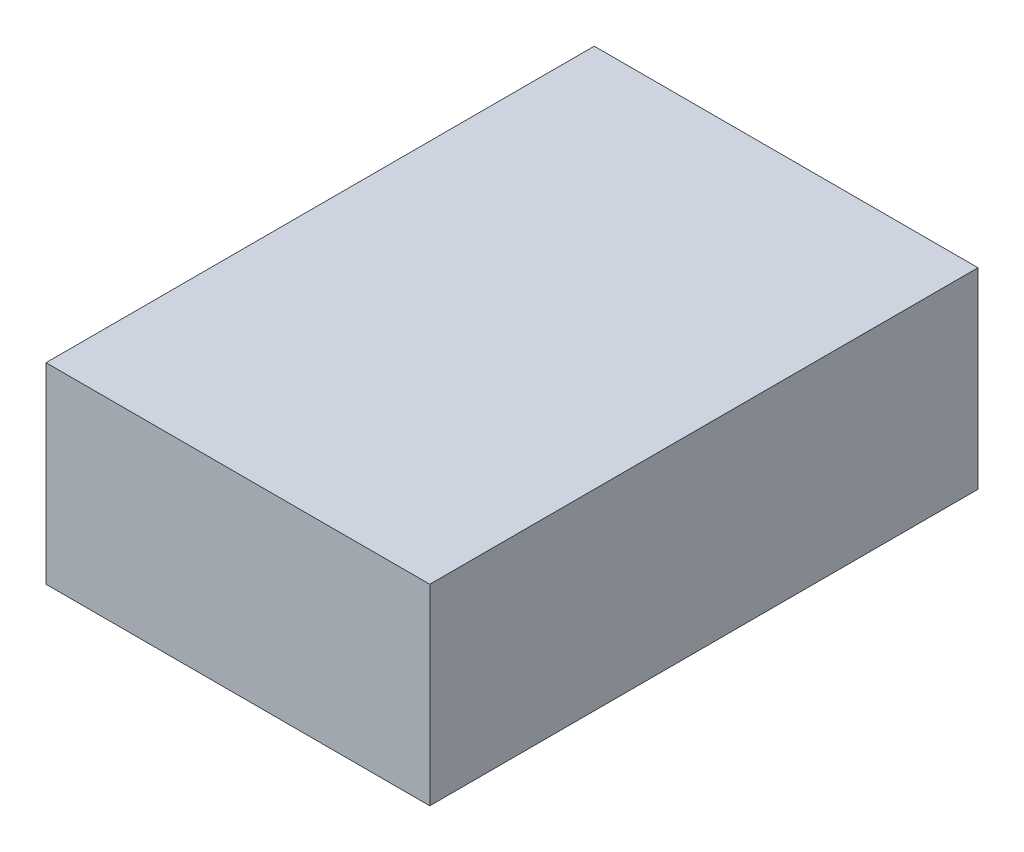
SolidWorks part; units mm, degrees
ref_plane "前视基准面" through (0, 0, 0) normal (0, 0, 1) x (1, 0, 0)
ref_plane "上视基准面" through (0, 0, 0) normal (0, 1, 0) x (1, 0, 0)
ref_plane "右视基准面" through (0, 0, 0) normal (1, 0, 0) x (0, 0, -1)
sketch "草图1" plane through (0, 0, 0) normal (1, 0, 0) x (0, 0, -1)
  line L1 (-40.4399, 37.1151) -> (59.5601, 37.1151)
  line L2 (-40.4399, 37.1151) -> (-40.4399, 2.1151)
  line L3 (-40.4399, 2.1151) -> (59.5601, 2.1151)
  line L4 (59.5601, 37.1151) -> (59.5601, 2.1151)
  dimension "D1" = 100
  dimension "D2" = 35
extrude "凸台-拉伸1" add sketch "草图1" along normal blind 70
